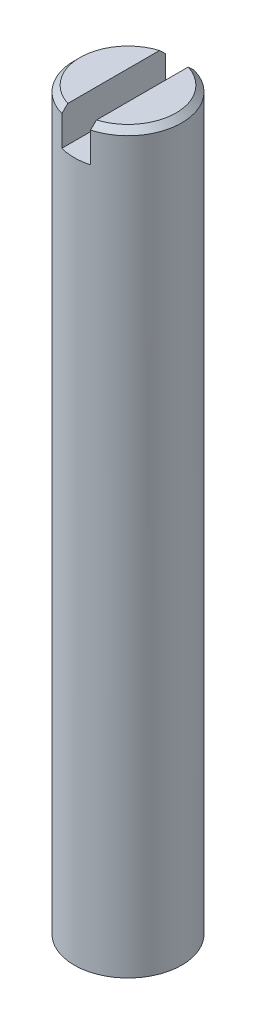
SolidWorks part; units mm, degrees
ref_plane "Front Plane" through (0, 0, 0) normal (0, 0, 1) x (1, 0, 0)
ref_plane "Top Plane" through (0, 0, 0) normal (0, 1, 0) x (1, 0, 0)
ref_plane "Right Plane" through (0, 0, 0) normal (1, 0, 0) x (0, 0, -1)
sketch "Sketch1" plane through (0, 0, 0) normal (0, 1, 0) x (1, 0, 0)
  circle A0 centre (0, 0) radius 0.1875
  dimension "D1" = 0.375
extrude "Boss-Extrude1" add sketch "Sketch1" along normal blind 2.563
sketch "Sketch2" plane through (0, 2.563, 0) normal (0, 1, 0) x (1, 0, 0)
  line L1 (-0.05, 0.2467) -> (0.05, 0.2467)
  line L2 (-0.05, 0.2467) -> (-0.05, -0.2467)
  line L3 (-0.05, -0.2467) -> (0.05, -0.2467)
  line L4 (0.05, 0.2467) -> (0.05, -0.2467)
  line L5 (-0.05, 0.2467) -> (0.05, -0.2467) construction
  line L6 (-0.05, -0.2467) -> (0.05, 0.2467) construction
  point P0 (0, 0)
  dimension "D1" = 0.1
extrude "Cut-Extrude1" cut sketch "Sketch2" against normal blind 0.125
chamfer "Chamfer1" distance 0.02 angle 45 2 edges at (-0.1875, 2.563, 0) (0.1875, 2.563, 0)
